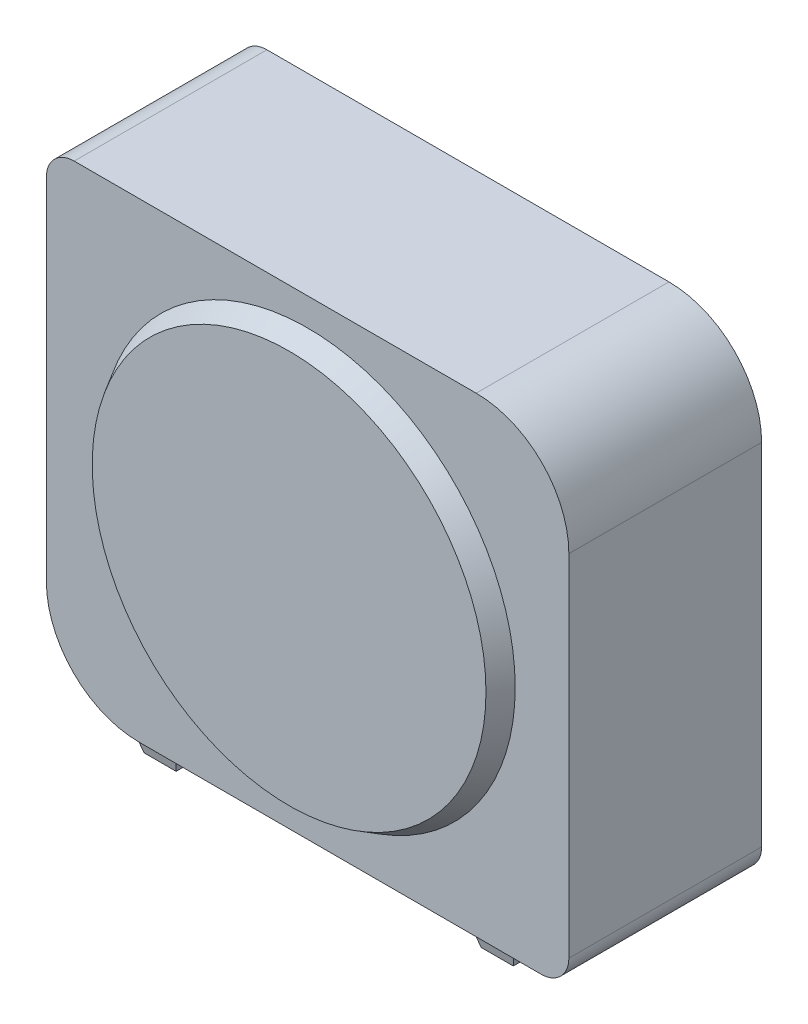
SolidWorks part; units mm, degrees
ref_plane "Front Plane" through (0, 0, 0) normal (0, 0, 1) x (1, 0, 0)
ref_plane "Top Plane" through (0, 0, 0) normal (0, 1, 0) x (1, 0, 0)
ref_plane "Right Plane" through (0, 0, 0) normal (1, 0, 0) x (0, 0, -1)
sketch "Sketch1" plane through (0, 0, 0) normal (0, 0, 1) x (1, 0, 0)
  line L1 (0, 0) -> (281.9, 0)
  line L2 (0, 0) -> (0, 254)
  line L3 (0, 254) -> (281.9, 254)
  line L4 (281.9, 0) -> (281.9, 254)
  dimension "D1" = 281.9
  dimension "D2" = 254
extrude "Boss-Extrude1" add sketch "Sketch1" along normal blind 104
sketch "Sketch3" plane through (0, 0, 104) normal (0, 0, 1) x (1, 0, 0)
  line L0 (0, 127) -> (140.95, 127) construction
  line L1 (0, 254) -> (0, 0) construction
  circle A0 centre (140.95, 127) radius 112
  dimension "D1" = 224
extrude "Boss-Extrude3" add sketch "Sketch3" along normal blind 10 draft 30
sketch "Sketch5" plane through (0, 0, 0) normal (0, 0, -1) x (-1, 0, 0)
  line L0 (0, 127) -> (-140.95, 127) construction
  line L1 (0, 254) -> (0, 0) construction
  circle A0 centre (-140.95, 127) radius 112
  dimension "D1" = 224
extrude "Boss-Extrude5" add sketch "Sketch5" along normal blind 10 draft 30
fillet "Fillet5" radius 50 1 edges at (281.9, 254, 52)
fillet "Fillet7" radius 15 1 edges at (0, 254, 52)
fillet "Fillet8" radius 15 1 edges at (281.9, 0, 52)
fillet "Fillet9" radius 50 1 edges at (0, 0, 52)
sketch "Sketch4" plane through (0, 0, 114) normal (0, 0, 1) x (1, 0, 0)
sketch "Sketch6" plane through (0, 0, 0) normal (0, -1, 0) x (1, 0, 0)
  line L0 (50, 104) -> (266.9, 104) construction
  line L1 (251.9, 104) -> (231.9, 104)
  line L2 (251.9, 104) -> (251.9, 0)
  line L3 (251.9, 0) -> (231.9, 0)
  line L4 (231.9, 104) -> (231.9, 0)
  line L5 (28.95, 0) -> (252.95, 0) construction
  line L6 (266.9, 0) -> (266.9, 104) construction
  line L7 (50, 0) -> (266.9, 0) construction
  line L8 (50, 104) -> (70, 104)
  line L9 (50, 104) -> (50, 0)
  line L10 (50, 0) -> (70, 0)
  line L11 (70, 104) -> (70, 0)
  dimension "D1" = 15
  dimension "D2" = 20
  dimension "D3" = 20
sketch "Sketch7" plane through (0, 0, 104) normal (0, 0, 1) x (1, 0, 0)
  line L0 (140.95, 127) -> (0, 127)
  line L1 (0, 239) -> (0, 50) construction
  line L2 (140.95, 127) -> (281.9, 127)
  line L3 (281.9, 15) -> (281.9, 204) construction
  line L4 (231.9, 254) -> (15, 254) construction
  line L5 (0, 127) -> (281.9, 127)
  line L6 (0, 127) -> (0, 254)
  line L7 (0, 254) -> (281.9, 254)
  line L8 (281.9, 127) -> (281.9, 254)
  dimension "D1" = 0
extrude "Boss-Extrude7" add sketch "Sketch6" along normal blind 5 draft 15
